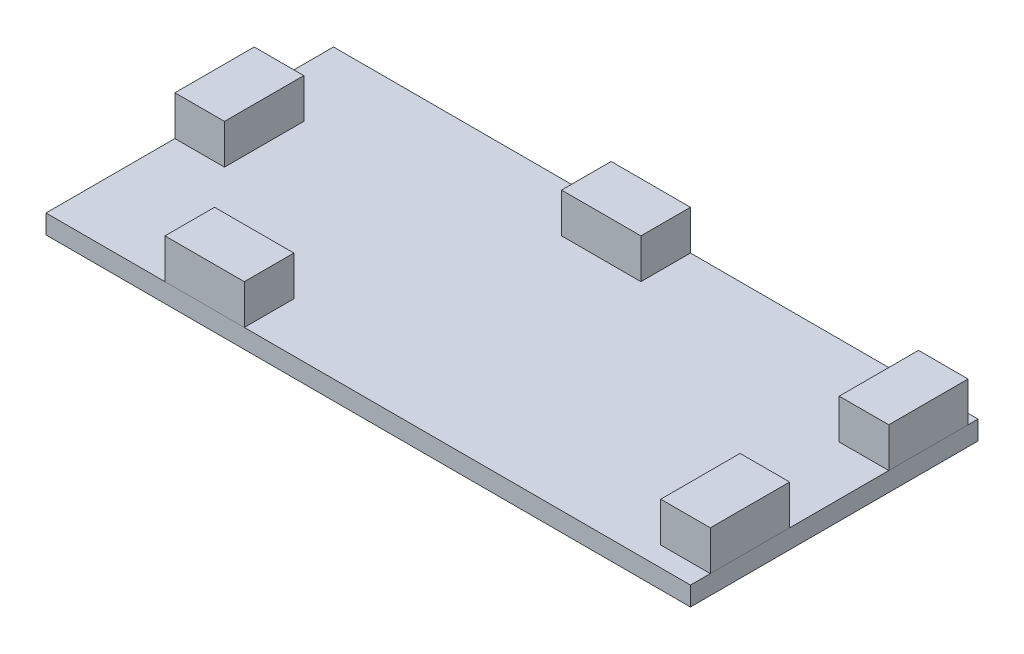
SolidWorks part; units mm, degrees
ref_plane "Front Plane" through (0, 0, 0) normal (0, 0, 1) x (1, 0, 0)
ref_plane "Top Plane" through (0, 0, 0) normal (0, 1, 0) x (1, 0, 0)
ref_plane "Right Plane" through (0, 0, 0) normal (1, 0, 0) x (0, 0, -1)
sketch "Sketch1" plane through (0, 0, 0) normal (0, 1, 0) x (1, 0, 0)
  line L1 (-25.7969, -11.5094) -> (25.7969, -11.5094)
  line L2 (-25.7969, -11.5094) -> (-25.7969, 11.5094)
  line L3 (-25.7969, 11.5094) -> (25.7969, 11.5094)
  line L4 (25.7969, -11.5094) -> (25.7969, 11.5094)
  line L5 (-25.7969, -11.5094) -> (25.7969, 11.5094) construction
  line L6 (-25.7969, 11.5094) -> (25.7969, -11.5094) construction
  point P0 (0, 0)
  dimension "D1" = 51.5938
  dimension "D2" = 23.0188
extrude "Boss-Extrude1" add sketch "Sketch1" along normal blind 1.524
sketch "Sketch2" plane through (0, 1.524, 0) normal (0, 1, 0) x (1, 0, 0)
  line L0 (25.7969, -11.5094) -> (25.7969, 11.5094) construction
  line L1 (25.7969, -9.9219) -> (21.8281, -9.9219)
  line L2 (25.7969, -9.9219) -> (25.7969, -3.5719)
  line L3 (25.7969, -3.5719) -> (21.8281, -3.5719)
  line L4 (21.8281, -9.9219) -> (21.8281, -3.5719)
  line L5 (25.7969, 11.5094) -> (-25.7969, 11.5094) construction
  line L6 (25.7969, 10.7156) -> (21.8281, 10.7156)
  line L7 (25.7969, 10.7156) -> (25.7969, 4.3656)
  line L8 (25.7969, 4.3656) -> (21.8281, 4.3656)
  line L9 (21.8281, 10.7156) -> (21.8281, 4.3656)
  line L10 (-3.5719, 11.5094) -> (2.7781, 11.5094)
  line L11 (-3.5719, 11.5094) -> (-3.5719, 7.5406)
  line L12 (-3.5719, 7.5406) -> (2.7781, 7.5406)
  line L13 (2.7781, 11.5094) -> (2.7781, 7.5406)
  line L14 (-25.7969, 11.5094) -> (-25.7969, -11.5094) construction
  line L15 (-25.7969, 5.1594) -> (-21.8281, 5.1594)
  line L16 (-25.7969, 5.1594) -> (-25.7969, -1.1906)
  line L17 (-25.7969, -1.1906) -> (-21.8281, -1.1906)
  line L18 (-21.8281, 5.1594) -> (-21.8281, -1.1906)
  line L19 (-25.7969, -11.5094) -> (25.7969, -11.5094) construction
  line L20 (-16.2719, -11.5094) -> (-9.9219, -11.5094)
  line L21 (-16.2719, -11.5094) -> (-16.2719, -7.5406)
  line L22 (-16.2719, -7.5406) -> (-9.9219, -7.5406)
  line L23 (-9.9219, -11.5094) -> (-9.9219, -7.5406)
  dimension "D1" = 6.35
  dimension "D2" = 3.9688
  dimension "D3" = 1.5875
  dimension "D4" = 7.9375
  dimension "D5" = 22.225
  dimension "D6" = 6.35
  dimension "D7" = 9.525
extrude "Boss-Extrude2" add sketch "Sketch2" along normal blind 3.175 separate body
